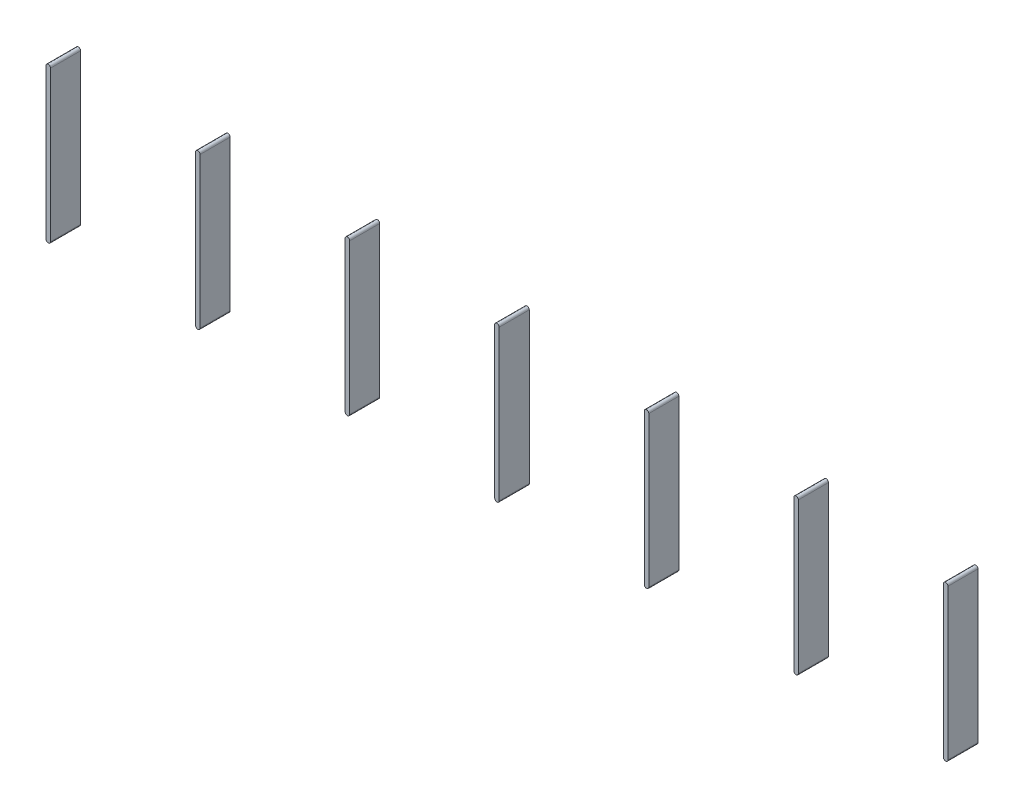
SolidWorks part; units mm, degrees
ref_plane "Front Plane" through (0, 0, 0) normal (0, 0, 1) x (1, 0, 0)
ref_plane "Top Plane" through (0, 0, 0) normal (0, 1, 0) x (1, 0, 0)
ref_plane "Right Plane" through (0, 0, 0) normal (1, 0, 0) x (0, 0, -1)
sketch "Sketch1" plane through (0, 0, 0) normal (0, 0, 1) x (1, 0, 0)
  line L0 (0, 0) -> (0, -20) construction
  line L1 (0.3, 0) -> (0.3, -20)
  line L2 (-0.3, 0) -> (-0.3, -20)
  line L3 (39.8, 0) -> (39.8, -20) construction
  line L4 (40.1, 0) -> (40.1, -20)
  line L5 (39.5, 0) -> (39.5, -20)
  line L6 (19.9, 0) -> (19.9, -20) construction
  line L7 (20.2, 0) -> (20.2, -20)
  line L8 (19.6, 0) -> (19.6, -20)
  line L9 (-19.9, 0) -> (-19.9, -20) construction
  line L10 (-19.6, 0) -> (-19.6, -20)
  line L11 (-20.2, 0) -> (-20.2, -20)
  line L12 (-39.8, 0) -> (-39.8, -20) construction
  line L13 (-39.5, 0) -> (-39.5, -20)
  line L14 (-40.1, 0) -> (-40.1, -20)
  line L15 (-59.7, 0) -> (-59.7, -20) construction
  line L16 (-59.4, 0) -> (-59.4, -20)
  line L17 (-60, 0) -> (-60, -20)
  line L18 (-79.6, 0) -> (-79.6, -20) construction
  line L19 (-79.3, 0) -> (-79.3, -20)
  line L20 (-79.9, 0) -> (-79.9, -20)
  line L21 (-79.6, -20) -> (-59.7, -20) construction
  line L22 (-59.7, -20) -> (-39.8, -20) construction
  line L23 (-39.8, -20) -> (-19.9, -20) construction
  line L24 (-19.9, -20) -> (0, -20) construction
  line L25 (0, -20) -> (19.9, -20) construction
  line L26 (19.9, -20) -> (39.8, -20) construction
  line L27 (40.1, -20) -> (40.2, -20) construction
  arc A0 (0.3, 0) -> (-0.3, 0) centre (0, 0) ccw
  arc A1 (-0.3, -20) -> (0.3, -20) centre (0, -20) ccw
  arc A2 (40.1, 0) -> (39.5, 0) centre (39.8, 0) ccw
  arc A3 (39.5, -20) -> (40.1, -20) centre (39.8, -20) ccw
  arc A4 (20.2, 0) -> (19.6, 0) centre (19.9, 0) ccw
  arc A5 (19.6, -20) -> (20.2, -20) centre (19.9, -20) ccw
  arc A6 (-19.6, 0) -> (-20.2, 0) centre (-19.9, 0) ccw
  arc A7 (-20.2, -20) -> (-19.6, -20) centre (-19.9, -20) ccw
  arc A8 (-39.5, 0) -> (-40.1, 0) centre (-39.8, 0) ccw
  arc A9 (-40.1, -20) -> (-39.5, -20) centre (-39.8, -20) ccw
  arc A10 (-59.4, 0) -> (-60, 0) centre (-59.7, 0) ccw
  arc A11 (-60, -20) -> (-59.4, -20) centre (-59.7, -20) ccw
  arc A12 (-79.3, 0) -> (-79.9, 0) centre (-79.6, 0) ccw
  arc A13 (-79.9, -20) -> (-79.3, -20) centre (-79.6, -20) ccw
  point P3 (0, -10)
  point P10 (39.8, -10)
  point P17 (19.9, -10)
  point P24 (-19.9, -10)
  point P31 (-39.8, -10)
  point P38 (-59.7, -10)
  point P45 (-79.6, -10)
  dimension "D9" = 0.3
  dimension "D2" = 19.9
  dimension "D1" = 0.1
  dimension "D8" = 20
  dimension "D3" = 19.9
  dimension "D4" = 19.9
  dimension "D5" = 19.9
  dimension "D6" = 19.9
  dimension "D7" = 19.9
extrude "Boss-Extrude1" add sketch "Sketch1" along normal blind 4
equation "\"D4@Sketch1\"=\"D2@Sketch1\""
equation "\"D5@Sketch1\"=\"D2@Sketch1\""
equation "\"D6@Sketch1\"=\"D2@Sketch1\""
equation "\"D7@Sketch1\"=\"D2@Sketch1\""
equation "\"D3@Sketch1\"=\"D2@Sketch1\""
